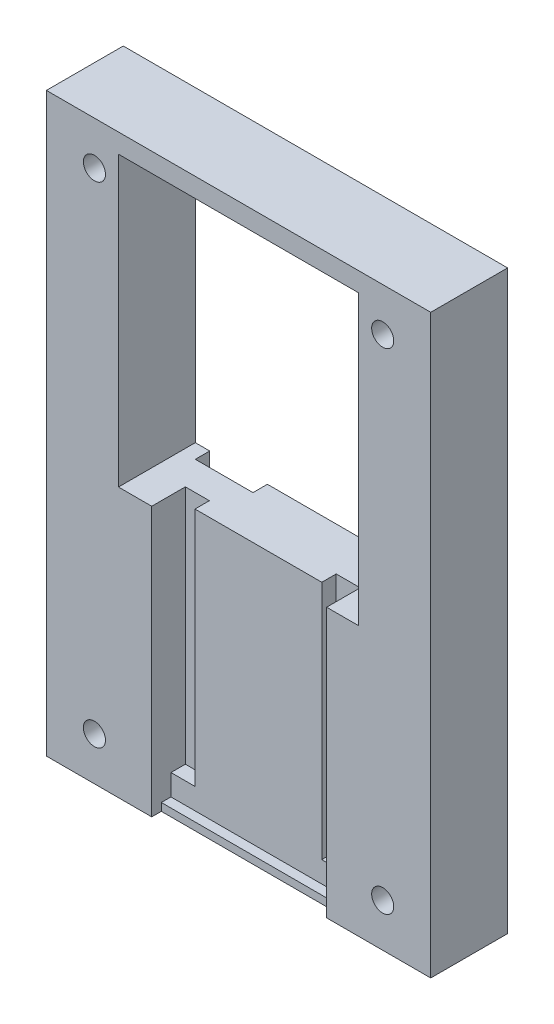
SolidWorks part; units mm, degrees
ref_plane "Front Plane" through (0, 0, 0) normal (1, 0, 0) x (0, 1, 0)
ref_plane "Top Plane" through (0, 0, 0) normal (0, 0, 1) x (0, 1, 0)
ref_plane "Right Plane" through (0, 0, 0) normal (0, 1, 0) x (-1, 0, 0)
sketch "Sketch1" plane through (0, 0, 0) normal (0, 0, 1) x (0, 1, 0)
  line L0 (0, -20) -> (60, -20) construction
  line L1 (0, 0) -> (60, 0)
  line L2 (0, 0) -> (0, -40)
  line L3 (0, -40) -> (60, -40)
  line L4 (60, 0) -> (60, -40)
  dimension "D1" = 60
  dimension "D2" = 40
extrude "Boss-Extrude1" add sketch "Sketch1" along normal blind 8
sketch "Sketch3" plane through (0, 0, 8) normal (0, 0, 1) x (1, 0, 0)
  line L0 (0, 55.5) -> (40, 55.5) construction
  line L1 (0, 60) -> (0, 0) construction
  line L2 (40, 0) -> (40, 60) construction
  line L3 (0, 4.5) -> (40, 4.5) construction
  line L4 (0, 30) -> (40, 30) construction
  line L5 (20, 60) -> (20, 0) construction
  line L6 (40, 60) -> (0, 60) construction
  line L7 (0, 0) -> (40, 0) construction
  circle A0 centre (5, 4.5) radius 1.15
  circle A1 centre (35, 4.5) radius 1.15
  circle A2 centre (5, 55.5) radius 1.15
  circle A3 centre (35, 55.5) radius 1.15
  dimension "D5" = 2.3
  dimension "D6" = 2.3
  dimension "D7" = 2.3
  dimension "D8" = 2.3
  dimension "D1" = 25.5
  dimension "D2" = 25.5
  dimension "D3" = 15
  dimension "D4" = 15
  dimension "D9" = 15
  dimension "D10" = 15
extrude "Cut-Extrude2" cut sketch "Sketch3" against normal through all
sketch "Sketch7" plane through (0, 0, 8) normal (0, 0, 1) x (1, 0, 0)
  line L0 (20, 60) -> (20, 0) construction
  line L1 (40, 60) -> (0, 60) construction
  line L2 (0, 0) -> (40, 0) construction
  line L4 (7.5, 58) -> (32.5, 58)
  line L5 (7.5, 58) -> (7.5, 28)
  line L6 (7.5, 28) -> (32.5, 28)
  line L7 (32.5, 58) -> (32.5, 28)
  point P10 (20, 28)
  dimension "D1" = 2
  dimension "D2" = 30
  dimension "D3" = 25
extrude "Cut-Extrude6" cut sketch "Sketch7" against normal through all
sketch "Sketch8" plane through (0, 0, 8) normal (0, 0, 1) x (1, 0, 0)
  line L1 (0, 0) -> (40, 0) construction
  line L4 (10.9625, 0) -> (29.1625, 0)
  line L5 (10.9625, 0) -> (10.9625, 45)
  line L6 (10.9625, 45) -> (29.1625, 45)
  line L7 (29.1625, 0) -> (29.1625, 45)
  dimension "D1" = 18.2
  dimension "D2" = 45
extrude "Cut-Extrude7" cut sketch "Sketch8" against normal blind 2
sketch "Sketch9" plane through (0, 0, 6) normal (0, 0, 1) x (1, 0, 0)
  line L1 (10.9625, 28) -> (13.4625, 28)
  line L2 (10.9625, 28) -> (10.9625, 3)
  line L3 (10.9625, 3) -> (13.4625, 3)
  line L4 (13.4625, 28) -> (13.4625, 3)
  line L5 (10.9625, 0) -> (29.1625, 0) construction
  line L6 (29.1625, 28) -> (26.6625, 28)
  line L7 (29.1625, 28) -> (29.1625, 3)
  line L8 (29.1625, 3) -> (26.6625, 3)
  line L9 (26.6625, 28) -> (26.6625, 3)
  dimension "D1" = 2.5
  dimension "D2" = 2.5
  dimension "D3" = 3
  dimension "D4" = 3
extrude "Cut-Extrude8" cut sketch "Sketch9" against normal blind 1.5
sketch "Sketch10" plane through (0, 0, 6) normal (0, 0, 1) x (1, 0, 0)
  line L0 (29.1625, 0) -> (29.1625, 28) construction
  line L1 (10.9625, 0) -> (29.1625, 0)
  line L2 (10.9625, 0) -> (10.9625, 0.8)
  line L3 (10.9625, 0.8) -> (29.1625, 0.8)
  line L4 (29.1625, 0) -> (29.1625, 0.8)
  dimension "D1" = 0.8
extrude "Boss-Extrude2" add sketch "Sketch10" along normal blind 1
sketch "Sketch11" plane through (0, 0, 0) normal (0, 0, -1) x (1, 0, 0)
  line L0 (0, -60) -> (0, 0) construction
  line L1 (26, -20.9) -> (21, -20.9)
  line L2 (26, -20.9) -> (26, -23.9)
  line L3 (26, -23.9) -> (21, -23.9)
  line L4 (21, -20.9) -> (21, -23.9)
  line L5 (26, -20.9) -> (21, -23.9) construction
  line L6 (26, -23.9) -> (21, -20.9) construction
  line L7 (0, 0) -> (40, 0) construction
  line L9 (9, -34) -> (15, -34)
  line L10 (9, -34) -> (9, -23)
  line L11 (9, -23) -> (15, -23)
  line L12 (15, -34) -> (15, -23)
  line L13 (40, 0) -> (40, -60) construction
  point P0 (23.5, -22.4)
  dimension "D1" = 16.5
  dimension "D2" = 22.4
  dimension "D3" = 5
  dimension "D4" = 3
  dimension "D5" = 34
  dimension "D6" = 23
  dimension "D7" = 9
  dimension "D8" = 15
extrude "Cut-Extrude9" cut sketch "Sketch11" against normal blind 1.5
